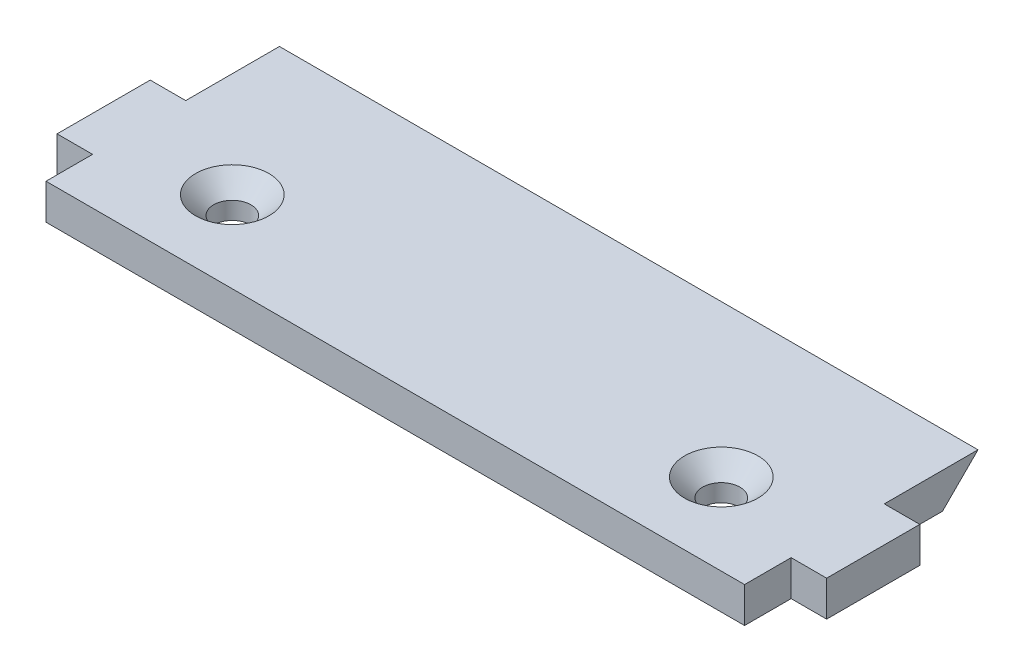
SolidWorks part; units mm, degrees
ref_plane "Front Plane" through (0, 0, 0) normal (0, 0, 1) x (1, 0, 0)
ref_plane "Top Plane" through (0, 0, 0) normal (0, 1, 0) x (1, 0, 0)
ref_plane "Right Plane" through (0, 0, 0) normal (1, 0, 0) x (0, 0, -1)
sketch "Sketch1" plane through (0, 0, 0) normal (0, 1, 0) x (1, 0, 0)
  line L0 (3.05, 12) -> (0, 7)
  line L1 (0, 0) -> (66.1, 0)
  line L2 (0, 0) -> (0, 20.05)
  line L3 (0, 20.05) -> (66.1, 20.05)
  line L4 (66.1, 0) -> (66.1, 20.05)
  line L7 (0, 12) -> (3.05, 12)
  line L8 (3.05, 20.05) -> (3.05, 12)
  line L11 (66.1, 12) -> (63.05, 12)
  line L12 (63.05, 20.05) -> (63.05, 12)
  line L13 (0, 0) -> (12.05, 0)
  line L14 (0, 0) -> (0, 7)
  line L15 (0, 7) -> (12.05, 7)
  line L16 (12.05, 0) -> (12.05, 7)
  line L17 (66.1, 0) -> (54.05, 0)
  line L18 (66.1, 0) -> (66.1, 7)
  line L19 (66.1, 7) -> (54.05, 7)
  line L20 (54.05, 0) -> (54.05, 7)
  line L21 (63.05, 12) -> (66.1, 7)
  line L23 (66.1, 0) -> (63.05, 0)
  line L24 (66.1, 0) -> (66.1, 4)
  line L25 (66.1, 4) -> (63.05, 4)
  line L26 (63.05, 0) -> (63.05, 4)
  line L27 (0, 0) -> (3.05, 0)
  line L28 (0, 0) -> (0, 4)
  line L29 (0, 4) -> (3.05, 4)
  line L30 (3.05, 0) -> (3.05, 4)
  circle A0 centre (12.05, 7) radius 1.5
  circle A1 centre (54.05, 7) radius 1.5
  point P25 (63.05, 17)
  point P26 (3.05, 20.05)
  point P27 (63.05, 20.05)
  dimension "D9" = 3
  dimension "D12" = 3
  dimension "D1" = 20.05
  dimension "D2" = 66.1
  dimension "D4" = 3.05
  dimension "D6" = 3.05
  dimension "D7" = 12.05
  dimension "D8" = 7
  dimension "D10" = 7
  dimension "D11" = 12.05
  dimension "D13" = 5
  dimension "D14" = 58.617
  dimension "D15" = 5
  dimension "D16" = 58.617
  dimension "D17" = 4
  dimension "D18" = 3.05
  dimension "D19" = 4
  dimension "D20" = 3.05
extrude "Boss-Extrude1" add sketch "Sketch1" along normal blind 3.05 contours L12 L3 L8 L7 L2 L1 L4 L11 | A0 L15 L2 L1 L16 | A1 L20 L1 L4 L19 | L11 L21 L4 | L7 L2 L0
hole_wizard "CSK for M3 Flat Head Machine Screw1" positions "Sketch4" profile "Sketch5" countersink size "M3" standard "ANSI Metric" end condition through all
sketch "Sketch4" plane through (0, 3.05, 0) normal (0, 1, 0) x (1, 0, 0)
  point P0 (12.05, 7)
sketch "Sketch5" plane through (12.05, 3.05, -7) normal (1, 0, 0) x (0, 0, 1)
  line L0 (0, 0) -> (0, 3.05)
  line L1 (0, 3.05) -> (1.6, 3.05)
  line L2 (1.6, 3.05) -> (1.6, 1.55)
  line L3 (1.6, 1.55) -> (3.15, 0)
  line L5 (3.15, 0) -> (0, 0)
  line L6 (-1.6, 1.55) -> (-3.15, 0) construction
  line L11 (0, -6.35) -> (0, 107.95) construction
  dimension "Thru Hole Dia." = 3.2
  dimension "Thru Hole Depth" = 3.05
  dimension "Near C'Sink Dia." = 6.3
  dimension "Near C'Sink Angle" = 90
hole_wizard "CSK for M3 Flat Head Machine Screw2" positions "Sketch6" profile "Sketch7" countersink size "M3" standard "ANSI Metric" end condition through all
sketch "Sketch6" plane through (0, 3.05, 0) normal (0, 1, 0) x (1, 0, 0)
  point P0 (54.05, 7)
sketch "Sketch7" plane through (54.05, 3.05, -7) normal (1, 0, 0) x (0, 0, 1)
  line L0 (0, 0) -> (0, 3.05)
  line L1 (0, 3.05) -> (1.6, 3.05)
  line L2 (1.6, 3.05) -> (1.6, 1.55)
  line L3 (1.6, 1.55) -> (3.15, 0)
  line L5 (3.15, 0) -> (0, 0)
  line L6 (-1.6, 1.55) -> (-3.15, 0) construction
  line L11 (0, -6.35) -> (0, 107.95) construction
  dimension "Thru Hole Dia." = 3.2
  dimension "Thru Hole Depth" = 3.05
  dimension "Near C'Sink Dia." = 6.3
  dimension "Near C'Sink Angle" = 90
sketch "Sketch8" plane through (63.05, 0, 0) normal (1, 0, 0) x (0, 0, -1)
  line L0 (20.05, 3.05) -> (17, 0)
  line L1 (20.05, 0) -> (12, 0) construction
  line L2 (17, 0) -> (20.05, 0)
  line L3 (20.05, 0) -> (20.05, 3.05)
  dimension "D1" = 45
extrude "Cut-Extrude1" cut sketch "Sketch8" against normal through all
